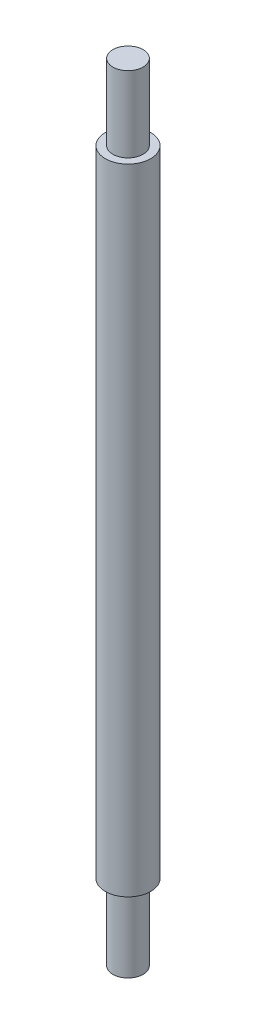
SolidWorks part; units mm, degrees
ref_plane "Front Plane" through (0, 0, 0) normal (0, 0, 1) x (1, 0, 0)
ref_plane "Top Plane" through (0, 0, 0) normal (0, 1, 0) x (1, 0, 0)
ref_plane "Right Plane" through (0, 0, 0) normal (1, 0, 0) x (0, 0, -1)
sketch "Sketch1" plane through (0, 0, 0) normal (0, 1, 0) x (1, 0, 0)
  circle A0 centre (0, 0) radius 2
  dimension "D1" = 4
extrude "Boss-Extrude1" add sketch "Sketch1" along normal blind 10
sketch "Sketch2" plane through (0, 10, 0) normal (0, 1, 0) x (1, 0, 0)
  circle A0 centre (0, 0) radius 3
  circle A1 centre (0, 0) radius 2
  circle A2 centre (0, 0) radius 2
  dimension "D2" = 6
  dimension "D1" = 0
extrude "Boss-Extrude2" add sketch "Sketch2" along normal blind 84 separate body contours A0
sketch "Sketch3" plane through (0, 94, 0) normal (0, 1, 0) x (1, 0, 0)
  circle A0 centre (0, 0) radius 2
  circle A1 centre (0, 0) radius 3
  circle A2 centre (0, 0) radius 3
  dimension "D2" = 4
  dimension "D1" = 0
extrude "Boss-Extrude3" add sketch "Sketch3" along normal blind 10 contours A0
